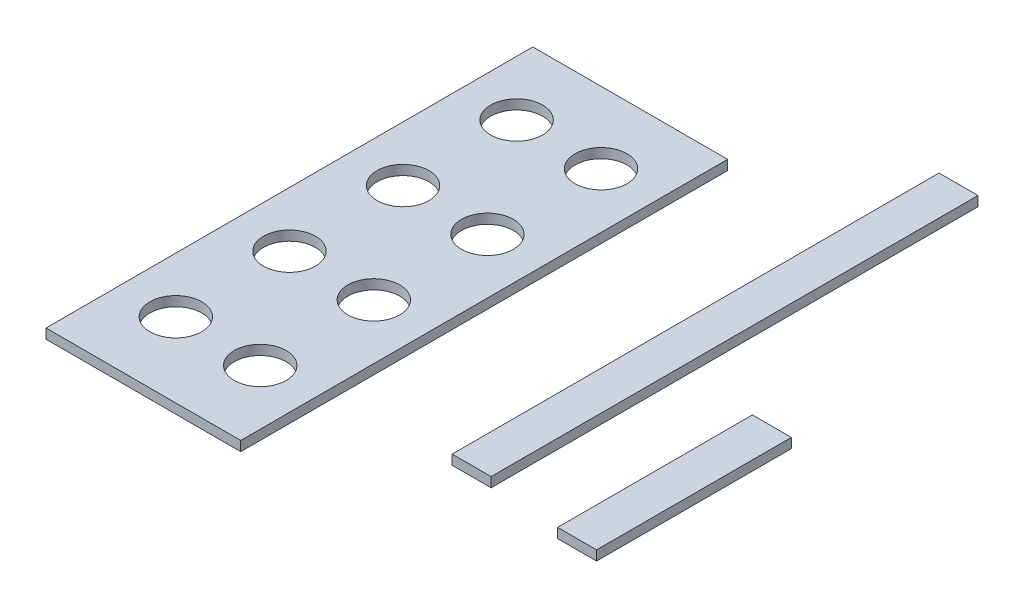
SolidWorks part; units mm, degrees
ref_plane "Front Plane" through (0, 0, 0) normal (0, 0, 1) x (1, 0, 0)
ref_plane "Top Plane" through (0, 0, 0) normal (0, 1, 0) x (1, 0, 0)
ref_plane "Right Plane" through (0, 0, 0) normal (1, 0, 0) x (0, 0, -1)
sketch "Sketch1" plane through (0, 0, 0) normal (0, 1, 0) x (1, 0, 0)
  line L1 (-38.3775, 137.6443) -> (21.6225, 137.6443)
  line L2 (-38.3775, 137.6443) -> (-38.3775, -12.3557)
  line L3 (-38.3775, -12.3557) -> (21.6225, -12.3557)
  line L4 (21.6225, 137.6443) -> (21.6225, -12.3557)
  dimension "D1" = 60
  dimension "D2" = 150
extrude "Boss-Extrude2" add sketch "Sketch1" along normal blind 3
sketch "Sketch2" plane through (0, 0, 0) normal (0, 1, 0) x (1, 0, 0)
  line L1 (57.8363, 166.5718) -> (69.8363, 166.5718)
  line L2 (57.8363, 166.5718) -> (57.8363, 16.5718)
  line L3 (57.8363, 16.5718) -> (69.8363, 16.5718)
  line L4 (69.8363, 166.5718) -> (69.8363, 16.5718)
  dimension "D1" = 12
  dimension "D2" = 150
extrude "Boss-Extrude4" add sketch "Sketch2" along normal blind 3 separate body
sketch "Sketch3" plane through (0, 0, 0) normal (0, 1, 0) x (1, 0, 0)
  line L1 (93.6296, 73.2668) -> (105.6296, 73.2668)
  line L2 (93.6296, 73.2668) -> (93.6296, 13.2668)
  line L3 (93.6296, 13.2668) -> (105.6296, 13.2668)
  line L4 (105.6296, 73.2668) -> (105.6296, 13.2668)
  dimension "D1" = 12
  dimension "D2" = 60
extrude "Boss-Extrude5" add sketch "Sketch3" along normal blind 3 separate body
sketch "Sketch4" plane through (0, 3, 0) normal (0, 1, 0) x (1, 0, 0)
  line L0 (-38.3775, -12.3557) -> (21.6225, -12.3557) construction
  line L1 (21.6225, -12.3557) -> (21.6225, 137.6443) construction
  line L2 (-38.3775, 137.6443) -> (-38.3775, -12.3557) construction
  circle A0 centre (4.6225, 10.6443) radius 8
  circle A1 centre (-21.3775, 10.6443) radius 8
  circle A2 centre (4.6225, 45.6443) radius 8
  circle A3 centre (-21.3775, 45.6443) radius 8
  circle A4 centre (4.6225, 80.6443) radius 8
  circle A5 centre (-21.3775, 80.6443) radius 8
  circle A6 centre (4.6225, 115.6443) radius 8
  circle A7 centre (-21.3775, 115.6443) radius 8
  dimension "D1" = 16
  dimension "D2" = 23
  dimension "D3" = 17
  dimension "D4" = 16
  dimension "D5" = 26
  dimension "D6" = 17
  dimension "D7" = 4
extrude "Cut-Extrude1" cut sketch "Sketch4" against normal blind 3
